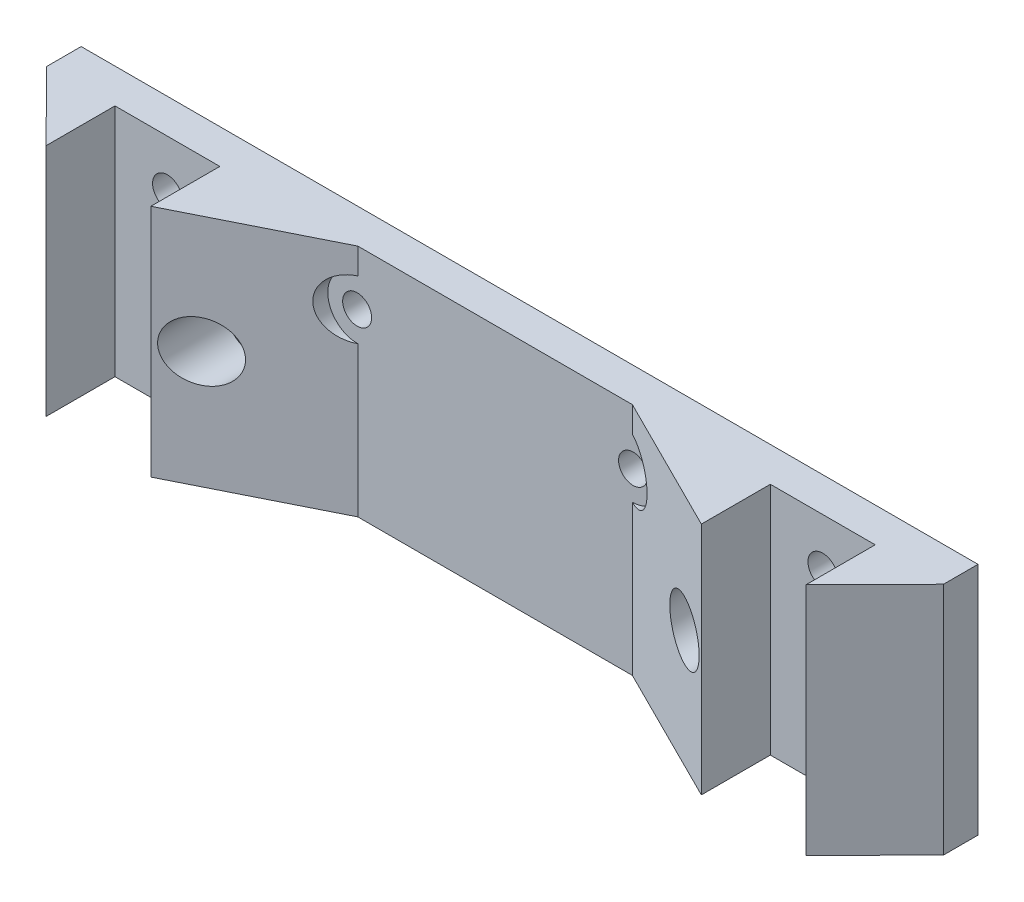
SolidWorks part; units mm, degrees
ref_plane "Front Plane" through (0, 0, 0) normal (0, 0, 1) x (1, 0, 0)
ref_plane "Top Plane" through (0, 0, 0) normal (0, 1, 0) x (1, 0, 0)
ref_plane "Right Plane" through (0, 0, 0) normal (1, 0, 0) x (0, 0, -1)
sketch "Sketch1" plane through (0, 0, 0) normal (0, 0, 1) x (1, 0, 0)
  line L0 (-75, 110.4999) -> (-55, 110.4999) construction
  line L1 (-65, 110.4999) -> (65, 110.4999)
  line L2 (-65, 110.4999) -> (-65, 76.4999)
  line L3 (-65, 76.4999) -> (65, 76.4999)
  line L4 (65, 110.4999) -> (65, 76.4999)
  line L5 (-65, 93.4999) -> (65, 93.4999) construction
  line L6 (-55, 210.9999) -> (-55, -210.9999) construction
  line L7 (55, -210.9999) -> (55, 210.9999) construction
  line L8 (-47.5, 103.4999) -> (-47.5, 83.4999) construction
  line L9 (-40, 210.9999) -> (-40, -210.9999) construction
  line L10 (0, 110.4999) -> (0, 76.4999) construction
  line L11 (47.5, 103.4999) -> (47.5, 83.4999) construction
  circle A1 centre (35, 93.4999) radius 2.1 construction
  circle A2 centre (20, 102.4999) radius 2.1 construction
  circle A3 centre (-35, 93.4999) radius 2.1 construction
  circle A4 centre (-20, 102.4999) radius 2.1 construction
  circle A5 centre (35, 93.4999) radius 2.1
  circle A6 centre (20, 102.4999) radius 2.1
  circle A7 centre (-35, 93.4999) radius 2.1
  circle A8 centre (-20, 102.4999) radius 2.1
  circle A9 centre (-47.5, 103.4999) radius 2.15
  circle A10 centre (-47.5, 83.4999) radius 2.15
  circle A11 centre (47.5, 83.4999) radius 2.15
  circle A12 centre (47.5, 103.4999) radius 2.15
  dimension "D5" = 10
  dimension "D6" = 10
  dimension "D7" = 4.3
  dimension "D1" = 34
  dimension "D2" = 10
  dimension "D3" = 10
  dimension "D4" = 7.5
extrude "Extrude1" add sketch "Sketch1" along normal blind 5
sketch "Sketch3" plane through (0, 76.4999, 0) normal (0, -1, 0) x (1, 0, 0)
  line L0 (-65, 5) -> (65, 5) construction
  line L1 (-65, 5) -> (-55.1, 5)
  line L4 (-55.1, 5) -> (-55.1, 15)
  line L5 (-39.9, 5) -> (-19.9, 5)
  line L6 (-39.9, 5) -> (-39.9, 15)
  line L9 (-65, 5) -> (-55.1, 15)
  line L10 (-39.9, 15) -> (-19.9, 5)
  line L11 (-55, 20) -> (-55, 5) construction
  line L12 (-40, 20) -> (-40, 5) construction
  line L13 (0, 5) -> (0, 14.4791) construction
  line L14 (39.9, 15) -> (19.9, 5)
  line L15 (65, 5) -> (55.1, 15)
  line L16 (39.9, 5) -> (39.9, 15)
  line L17 (39.9, 5) -> (19.9, 5)
  line L18 (55.1, 5) -> (55.1, 15)
  line L19 (65, 5) -> (55.1, 5)
  dimension "D1" = 0.1
  dimension "D2" = 0.1
  dimension "D3" = 10
  dimension "D4" = 10
  dimension "D5" = 20
extrude "Extrude2" add sketch "Sketch3" against normal blind 34
sketch "Sketch4" plane through (0, 0, 5) normal (0, 0, 1) x (1, 0, 0)
  line L0 (19.9, 104.5975) -> (19.9, 100.4023) construction
  circle A0 centre (-20, 102.4999) radius 4.25
  circle A1 centre (19.9, 102.4999) radius 4.25
  circle A2 centre (-35, 93.4999) radius 4.25
  circle A3 centre (35, 93.4999) radius 4.25
  dimension "D1" = 8.5
extrude "Cut-Extrude1" cut sketch "Sketch4" along normal blind 34
